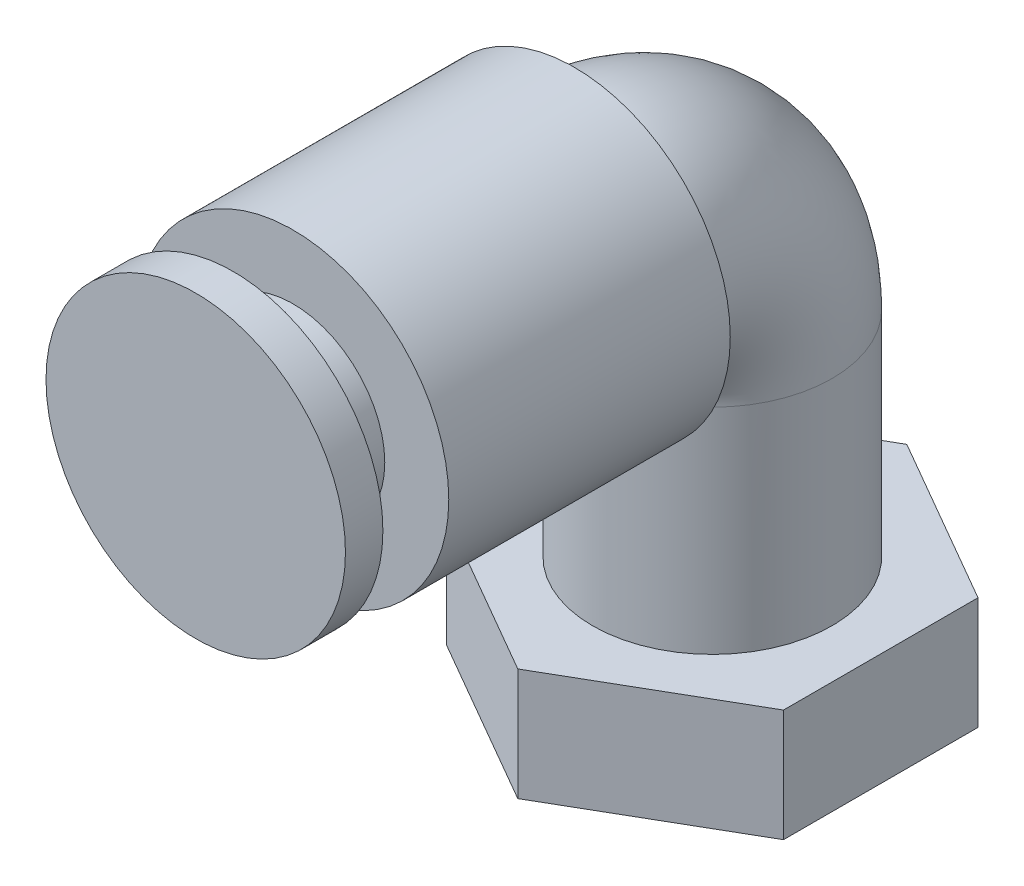
SolidWorks part; units mm, degrees
ref_plane "Front Plane" through (0, 0, 0) normal (0, 0, 1) x (1, 0, 0)
ref_plane "Top Plane" through (0, 0, 0) normal (0, 1, 0) x (1, 0, 0)
ref_plane "Right Plane" through (0, 0, 0) normal (1, 0, 0) x (0, 0, -1)
sketch "Sketch1" plane through (0, 0, 0) normal (0, 1, 0) x (1, 0, 0)
  line L1 (0, 8.2489) -> (-7.1438, 4.1244)
  line L2 (-7.1438, 4.1244) -> (-7.1437, -4.1244)
  line L3 (-7.1437, -4.1244) -> (0, -8.2489)
  line L4 (0, -8.2489) -> (7.1438, -4.1244)
  line L5 (7.1438, -4.1244) -> (7.1437, 4.1244)
  line L6 (7.1437, 4.1244) -> (0, 8.2489)
  circle A0 centre (0, 0) radius 7.1438 construction
  dimension "D1" = 14.2875
extrude "Boss-Extrude1" add sketch "Sketch1" along normal blind 4.7625
sketch "Sketch2" plane through (0, 4.7625, 0) normal (0, 1, 0) x (1, 0, 0)
  circle A0 centre (0, 0) radius 5.08
  dimension "D1" = 10.16
sketch "Sketch3" plane through (0, 0, 0) normal (1, 0, 0) x (0, 0, -1)
  line L0 (0, 4.7625) -> (0, 13.843)
  line L1 (5.08, 4.7625) -> (-5.08, 4.7625) construction
  line L2 (-5.207, 19.05) -> (-17.78, 19.05)
  arc A0 (0, 13.843) -> (-5.207, 19.05) centre (-5.207, 13.843) ccw
  dimension "D2" = 5.207
  dimension "D1" = 14.2875
  dimension "D3" = 17.78
sweep "Sweep3" add profiles "Sketch2" path "Sketch3"
sketch "Sketch4" plane through (0, 0, 17.78) normal (0, 0, 1) x (1, 0, 0)
  circle A0 centre (0, 19.05) radius 6.604
  dimension "D1" = 13.208
extrude "Boss-Extrude2" add sketch "Sketch4" against normal blind 11.938
sketch "Sketch5" plane through (0, 0, 17.78) normal (0, 0, 1) x (1, 0, 0)
  circle A0 centre (0, 19.05) radius 3.8898
  dimension "D1" = 7.7797
extrude "Boss-Extrude3" add sketch "Sketch5" along normal blind 2.54
sketch "Sketch6" plane through (0, 0, 20.32) normal (0, 0, 1) x (1, 0, 0)
  circle A0 centre (0, 19.05) radius 6.35
  dimension "D1" = 12.7
extrude "Boss-Extrude4" add sketch "Sketch6" along normal blind 1.5875
